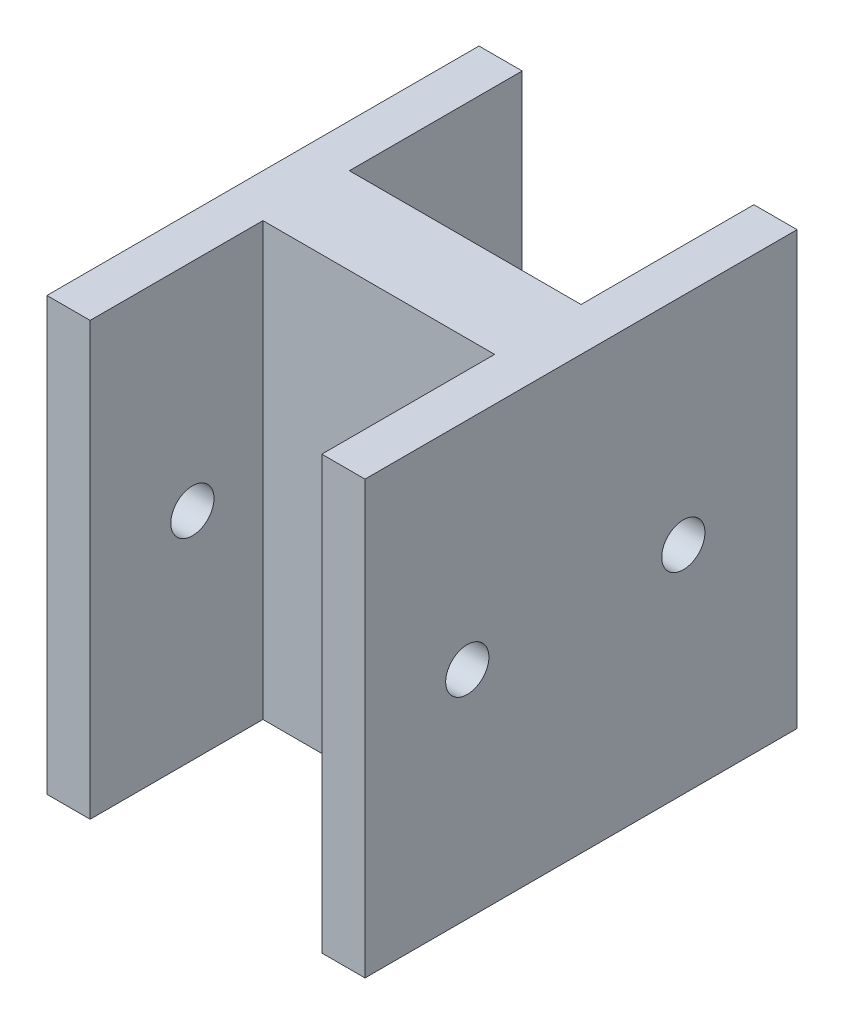
SolidWorks part; units mm, degrees
ref_plane "Front Plane" through (0, 0, 0) normal (0, 0, 1) x (1, 0, 0)
ref_plane "Top Plane" through (0, 0, 0) normal (0, 1, 0) x (1, 0, 0)
ref_plane "Right Plane" through (0, 0, 0) normal (1, 0, 0) x (0, 0, -1)
sketch "Sketch1" plane through (0, 0, 0) normal (0, 1, 0) x (1, 0, 0)
  line L0 (-12.3188, 7.6329) -> (-12.3188, -2.3671)
  line L1 (-12.3188, -2.3671) -> (-11.3188, -2.3671)
  line L2 (-11.3188, -2.3671) -> (-11.3188, 1.6329)
  line L3 (-11.3188, 1.6329) -> (-5.9565, 1.6329)
  line L4 (-5.9565, 1.6329) -> (-5.9565, -2.3671)
  line L5 (-5.9565, -2.3671) -> (-4.9565, -2.3671)
  line L6 (-4.9565, -2.3671) -> (-4.9565, 7.6329)
  line L7 (-4.9565, 7.6329) -> (-5.9565, 7.6329)
  line L8 (-5.9565, 7.6329) -> (-5.9565, 3.6329)
  line L9 (-5.9565, 3.6329) -> (-11.3188, 3.6329)
  line L10 (-11.3188, 3.6329) -> (-11.3188, 7.6329)
  line L11 (-11.3188, 7.6329) -> (-12.3188, 7.6329)
  dimension "D1" = 10
  dimension "D2" = 10
  dimension "D3" = 2
  dimension "D4" = 4
  dimension "D5" = 4
  dimension "D6" = 1
  dimension "D7" = 1
  dimension "D8" = 1
extrude "Boss-Extrude2" add sketch "Sketch1" along normal blind 10
sketch "Sketch2" plane through (-4.9565, 0, 0) normal (1, 0, 0) x (0, 0, -1)
  line L0 (-2.3671, 5) -> (7.6329, 5) construction
  line L1 (-2.3671, 10) -> (-2.3671, 0) construction
  line L2 (7.6329, 10) -> (7.6329, 0) construction
  line L3 (0, 0) -> (0, 10) construction
  line L4 (-2.3671, 10) -> (7.6329, 10) construction
  circle A0 centre (0, 5) radius 0.5
  dimension "D1" = 1
extrude "Cut-Extrude1" cut sketch "Sketch2" against normal through all
pattern_linear "LPattern1" count 2 spacing 5 along (0, 0, -1) of "Cut-Extrude1"
